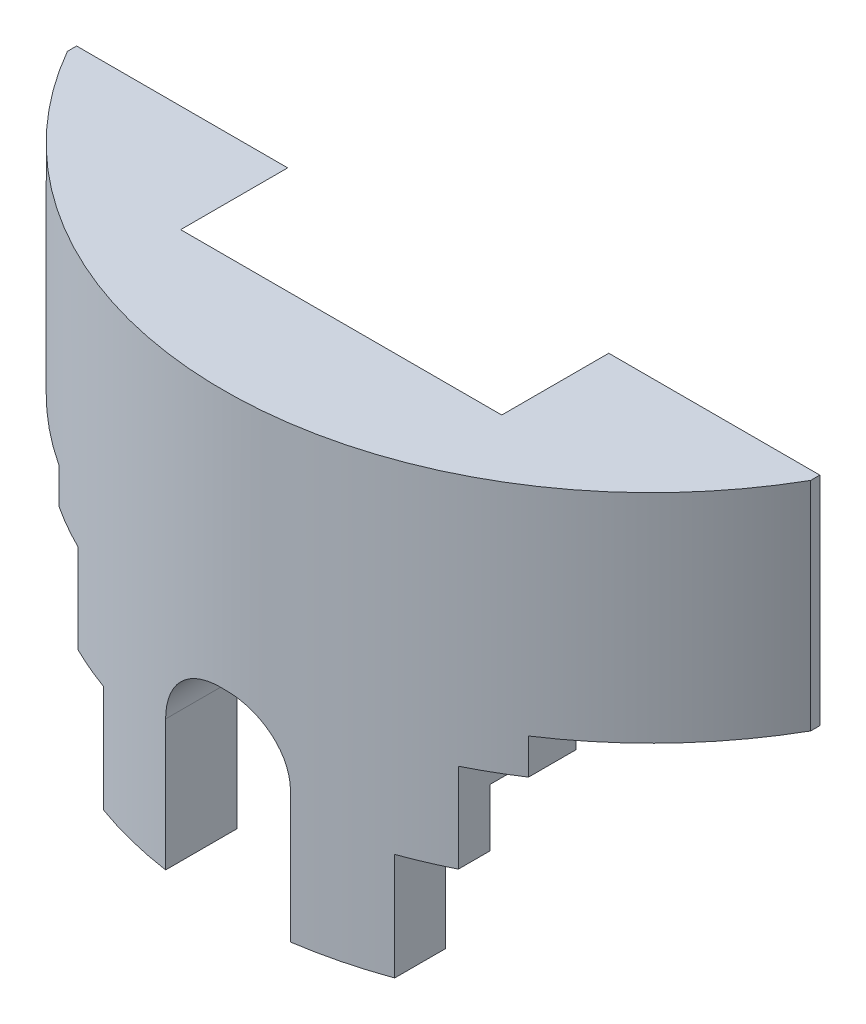
SolidWorks part; units mm, degrees
material "Pure Lead"
ref_plane "Front Plane" through (0, 0, 0) normal (0, 0, 1) x (1, 0, 0)
ref_plane "Top Plane" through (0, 0, 0) normal (0, 1, 0) x (1, 0, 0)
ref_plane "Right Plane" through (0, 0, 0) normal (1, 0, 0) x (0, 0, -1)
sketch "Sketch1" plane through (0, 0, 0) normal (0, 1, 0) x (1, 0, 0)
  line L0 (-62.5, -34.2) -> (-62.5, -35.7456)
  line L1 (-62.5, -34.2) -> (62.5, -34.2)
  line L2 (62.5, -34.2) -> (62.5, -35.7456)
  arc A0 (-62.5, -35.7456) -> (62.5, -35.7456) centre (0, 0) ccw
  dimension "D1" = 144
  dimension "D2" = 125
  dimension "D3" = 34.2
extrude "Boss-Extrude1" add sketch "Sketch1" against normal blind 36.5
sketch "Sketch2" plane through (0, -36.5, 0) normal (0, -1, 0) x (1, 0, 0)
  line L0 (-39.5, 60.1976) -> (-39.5, 34.2)
  line L1 (62.5, 34.2) -> (-62.5, 34.2) construction
  line L2 (-39.5, 34.2) -> (39.5, 34.2)
  line L3 (39.5, 34.2) -> (39.5, 60.1976)
  arc A0 (62.5, 35.7456) -> (-62.5, 35.7456) centre (0, 0) ccw construction
  arc A1 (-39.5, 60.1976) -> (39.5, 60.1976) centre (0, 0) cw
  line M2 (-62.5, 34.2) -> (62.5, 34.2)
  arc M4 (62.5, 35.7456) -> (-62.5, 35.7456) centre (0, 0) ccw
  dimension "D1" = 79
extrude "Boss-Extrude2" add sketch "Sketch2" along normal blind 6 contours L3 L0 M2 M4
sketch "Sketch3" plane through (0, -42.5, 0) normal (0, -1, 0) x (1, 0, 0)
  line L0 (-32, 64.4981) -> (-32, 34.2)
  line L1 (-39.5, 34.2) -> (39.5, 34.2) construction
  line L2 (-32, 34.2) -> (32, 34.2)
  line L3 (32, 34.2) -> (32, 64.4981)
  arc A0 (39.5, 60.1976) -> (-39.5, 60.1976) centre (0, 0) ccw construction
  arc A1 (32, 64.4981) -> (-32, 64.4981) centre (0, 0) ccw
  dimension "D1" = 64
extrude "Boss-Extrude3" add sketch "Sketch3" along normal blind 15
sketch "Sketch4" plane through (0, -57.5, 0) normal (0, -1, 0) x (1, 0, 0)
  line L0 (-24.5, 34.2) -> (-24.5, 67.7034)
  line L1 (-32, 34.2) -> (32, 34.2) construction
  line L2 (-24.5, 34.2) -> (24.5, 34.2)
  line L3 (24.5, 34.2) -> (24.5, 67.7034)
  arc A0 (32, 64.4981) -> (-32, 64.4981) centre (0, 0) ccw construction
  arc A1 (-24.5, 67.7034) -> (24.5, 67.7034) centre (0, 0) cw
  dimension "D1" = 49
extrude "Boss-Extrude4" add sketch "Sketch4" along normal blind 18
sketch "Sketch7" plane through (0, 0, 34.2) normal (0, 0, -1) x (-1, 0, 0)
  line L0 (0, -75.5) -> (0, -53.5) construction
  line L1 (24.5, -75.5) -> (-24.5, -75.5) construction
  line L2 (-32.5, -53.5) -> (-32.5, -86)
  line L3 (-32.5, -86) -> (32.5, -86)
  line L4 (32.5, -86) -> (32.5, -53.5)
  arc A0 (32.5, -53.5) -> (-32.5, -53.5) centre (0, -53.5) ccw
  dimension "D2" = 65
  dimension "D1" = 22
extrude "Cut-Extrude2" cut sketch "Sketch7" against normal blind 25
sketch "Sketch5" plane through (0, -75.5, 0) normal (0, -1, 0) x (1, 0, 0)
  line L0 (-24.5, 34.2) -> (24.5, 34.2) construction
  line L1 (-10.5, 34.2) -> (10.5, 34.2)
  line L2 (-10.5, 34.2) -> (-10.5, 72)
  line L3 (-10.5, 72) -> (10.5, 72)
  line L4 (10.5, 34.2) -> (10.5, 72)
  arc A0 (24.5, 67.7034) -> (-24.5, 67.7034) centre (0, 0) ccw construction
  point P6 (0, 72)
  point P10 (0, 72)
  dimension "D1" = 21
extrude "Cut-Extrude1" cut sketch "Sketch5" against normal blind 32
fillet "Fillet1" radius 10 2 edges at (-10.5, -43.5, 65.2151) (10.5, -43.5, 65.2151)
sketch "Sketch8" plane through (0, 0, 34.2) normal (0, 0, -1) x (-1, 0, 0)
  line L0 (-27, -22) -> (27, -22) construction
  line L1 (-27, 0) -> (27, 0)
  line L2 (-27, -44) -> (27, -44)
  line L3 (-62.5, 0) -> (62.5, 0) construction
  arc A0 (-27, 0) -> (-27, -44) centre (-27, -22) ccw
  arc A1 (27, -44) -> (27, 0) centre (27, -22) ccw
  point P2 (0, -22)
  point P10 (0, 0)
  dimension "D1" = 22
  dimension "D2" = 54
extrude "Cut-Extrude3" cut sketch "Sketch8" against normal blind 18
sketch "Sketch9" plane through (0, 0, 34.2) normal (0, 0, -1) x (-1, 0, 0)
  line L1 (-43.2673, -38.5701) -> (43.5558, -38.5701)
  line L2 (-43.2673, -38.5701) -> (-43.2673, -49.7953)
  line L3 (-43.2673, -49.7953) -> (43.5558, -49.7953)
  line L4 (43.5558, -38.5701) -> (43.5558, -49.7953)
extrude "Cut-Extrude4" cut sketch "Sketch9" against normal up to surface (18 mm away) up to face at (0, -33.5816, 52.2)
equation "\"smallPulleyTeeth\"= 30"
equation "\"largePulleyTeeth\"= 30"
equation "\"eighthThick\"= 3.0mm"
equation "\"sixteenthThick\"= 1.7mm"
equation "\"quarterThick\"=6.0mm"
equation "\"OD\"= 145mm"
equation "\"puckAngle\"= 60.5deg"
equation "\"puckDiam\"= 76.5mm"
equation "\"puckDist\"= 85mm"
equation "\"scoopFillet\"= 5mm"
equation "\"axlePress\"= 5.9mm"
equation "\"press\"= 0.2mm"
equation "\"wheelClear\"= 0.3mm"
equation "\"10-32clear\"= 4.8mm"
equation "\"10-32tap\"= 4.45mm"
equation "\"6-32clear\"= 3.3mm"
equation "\"8-32clear\"= 4.0mm"
equation "\"4-40clear\"= 3.0mm"
equation "\"wheelHeight\"= 22mm"
equation "\"wheelWell\"= 65mm"
equation "\"ledSmall\"= 3.1mm"
equation "\"ledLarge\"= 4.2mm"
equation "\"ledLength\"= 4.2mm"
equation "\"4-40close\"= 2.7mm"
equation "\"4-40nutThick\"= 2.2mm"
equation "\"4-40nutWidth\"= 6.2mm"
equation "\"4-40insertHeight\"= 3.5mm"
equation "\"4-40insert\"= 4mm"
equation "\"D1@Sketch1\"=\"OD\"-1"
